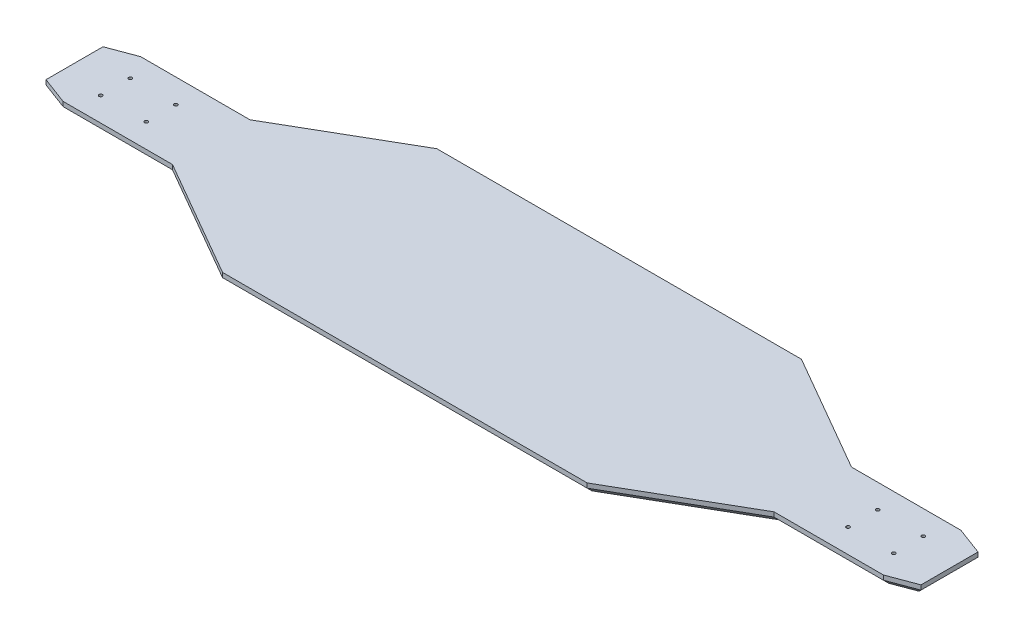
SolidWorks part; units mm, degrees
ref_plane "Front Plane" through (0, 0, 0) normal (0, 0, 1) x (1, 0, 0)
ref_plane "Top Plane" through (0, 0, 0) normal (0, 1, 0) x (1, 0, 0)
ref_plane "Right Plane" through (0, 0, 0) normal (1, 0, 0) x (0, 0, -1)
sketch "Sketch1" plane through (0, 0, 0) normal (0, 1, 0) x (1, 0, 0)
  line L0 (-241.1419, 54.734) -> (368.336, 54.734) construction
  line L1 (-241.1419, 15.0465) -> (-241.1419, 94.4215)
  line L2 (114.336, -94.491) -> (368.336, -94.491)
  line L3 (368.336, -94.491) -> (368.336, 54.734) construction
  line L4 (-50.6419, 108.709) -> (114.336, 203.959)
  line L5 (-203.0419, 108.709) -> (-241.1419, 94.4215)
  line L6 (-203.0419, 108.709) -> (-50.6419, 108.709)
  line L7 (-203.0419, 0.759) -> (-50.6419, 0.759)
  line L8 (114.336, 203.959) -> (368.336, 203.959)
  line L9 (787.3138, 0.759) -> (622.336, -94.491)
  line L10 (-203.0419, 0.759) -> (-241.1419, 15.0465)
  line L11 (-50.6419, 0.759) -> (114.336, -94.491)
  line L12 (939.7138, 0.759) -> (977.8138, 15.0465)
  line L13 (622.336, 203.959) -> (368.336, 203.959)
  line L14 (939.7138, 0.759) -> (787.3138, 0.759)
  line L15 (939.7138, 108.709) -> (787.3138, 108.709)
  line L16 (939.7138, 108.709) -> (977.8138, 94.4215)
  line L17 (787.3138, 108.709) -> (622.336, 203.959)
  line L18 (622.336, -94.491) -> (368.336, -94.491)
  line L19 (977.8138, 15.0465) -> (977.8138, 94.4215)
  dimension "D2" = 149.225
  dimension "D3" = 152.4
  dimension "D4" = 38.1
  dimension "D5" = 254
  dimension "D6" = 79.375
  dimension "D7" = 150
  dimension "D8" = 14.2875
  dimension "D10" = 190.5
extrude "Boss-Extrude1" add sketch "Sketch1" along normal blind 15.24
sketch "Sketch2" plane through (0, 0, 0) normal (0, -1, 0) x (-1, 0, 0)
  line L0 (241.1419, 54.734) -> (-37.1273, 54.734) construction
  line L1 (241.1419, 94.4215) -> (241.1419, 15.0465) construction
  line L2 (-368.336, -94.491) -> (-368.336, 203.959) construction
  line L3 (-114.336, -94.491) -> (-622.336, -94.491) construction
  line L4 (-622.336, 203.959) -> (-114.336, 203.959) construction
  line L5 (120.4919, 75.3715) -> (120.4919, 34.0965) construction
  line L6 (120.4919, 34.0965) -> (183.9919, 34.0965) construction
  line L7 (183.9919, 34.0965) -> (183.9919, 75.3715) construction
  line L8 (183.9919, 75.3715) -> (120.4919, 75.3715) construction
  circle A0 centre (183.9919, 34.0965) radius 2.3813
  circle A1 centre (183.9919, 75.3715) radius 2.3813
  circle A2 centre (120.4919, 75.3715) radius 2.3812
  circle A3 centre (120.4919, 34.0965) radius 2.3813
  circle A4 centre (-857.1638, 75.3715) radius 2.3813
  circle A5 centre (-920.6638, 75.3715) radius 2.3812
  circle A6 centre (-920.6638, 34.0965) radius 2.3812
  circle A7 centre (-857.1638, 34.0965) radius 2.3812
  point P29 (50.6419, 108.709)
  dimension "D1" = 57.15
  dimension "D2" = 63.5
  dimension "D3" = 41.275
  dimension "D4" = 20.6375
extrude "Cut-Extrude1" cut sketch "Sketch2" against normal blind 15.24
chamfer "Chamfer1" distance 8.89 angle 45 16 edges at (-126.8419, 0, -0.759) (-222.0919, 0, -7.9028) (-241.1419, 0, -54.734) (-222.0919, 0, -101.5653) (-126.8419, 0, -108.709) (31.8471, 0, -156.334) (31.8471, 0, 46.866) (368.336, 0, 94.491) (704.8249, 0, 46.866) (863.5138, 0, -0.759) (958.7638, 0, -7.9028) (977.8138, 0, -54.734) (958.7638, 0, -101.5653) (863.5138, 0, -108.709) (704.8249, 0, -156.334) (368.336, 0, -203.959)
sketch "Sketch3" plane through (0, 0, 0) normal (0, -1, 0) x (1, 0, 0)
  line L0 (962.5738, -54.734) -> (-232.2519, -54.734) construction
  line L1 (-232.2519, -21.2073) -> (-232.2519, -88.2607) construction
  line L2 (368.336, -195.069) -> (368.336, 85.601) construction
  line L3 (116.7181, -195.069) -> (619.9539, -195.069) construction
  line L4 (619.9539, 85.601) -> (116.7181, 85.601) construction
  line L5 (277.3193, -181.734) -> (277.3193, -54.734) construction
  line L6 (270.9693, -175.384) -> (127.036, -175.384) construction
  line L7 (270.9693, -175.384) -> (270.9693, -54.734) construction
  line L8 (114.336, -188.084) -> (114.336, -54.734) construction
  line L9 (120.686, -181.734) -> (120.686, -54.734) construction
  line L10 (120.686, -181.734) -> (277.3193, -181.734) construction
  line L11 (127.036, -175.384) -> (127.036, -54.734) construction
  line L12 (283.6693, -188.084) -> (283.6693, -54.734) construction
  line L13 (453.0027, -195.069) -> (453.0027, -54.734) construction
  line L14 (199.0027, -181.734) -> (199.0027, -54.734) construction
  line L15 (188.4193, -175.384) -> (188.4193, -143.634) construction
  line L16 (188.4193, -143.634) -> (137.6193, -143.634) construction
  line L17 (137.6193, -143.634) -> (137.6193, -175.384) construction
  line L18 (137.6193, -175.384) -> (188.4193, -175.384) construction
  line L20 (163.0193, -175.384) -> (163.0193, -54.734) construction
  line L32 (-118.1106, -34.0965) -> (-232.2519, -34.0965) construction
  line L33 (-120.4919, -75.3715) -> (-232.2519, -75.3715) construction
  line L36 (120.121, 72.901) -> (-44.8568, -22.349)
  line L37 (-44.8568, -22.349) -> (-199.1268, -22.349)
  line L38 (-199.1268, -22.349) -> (-219.5519, -30.0084)
  line L39 (-219.5519, -30.0084) -> (-219.5519, -79.4596)
  line L40 (-219.5519, -79.4596) -> (-199.1268, -87.119)
  line L41 (-199.1268, -87.119) -> (-44.8568, -87.119)
  line L42 (-44.8568, -87.119) -> (120.121, -182.369)
  line L43 (120.121, -182.369) -> (616.551, -182.369)
  line L44 (616.551, -182.369) -> (781.5288, -87.119)
  line L45 (781.5288, -87.119) -> (935.7988, -87.119)
  line L46 (935.7988, -87.119) -> (956.2238, -79.4596)
  line L47 (956.2238, -79.4596) -> (956.2238, -30.0084)
  line L80 (956.2238, -30.0084) -> (935.7988, -22.349)
  line L81 (935.7988, -22.349) -> (781.5288, -22.349)
  line L82 (781.5288, -22.349) -> (616.551, 72.901)
  line L83 (616.551, 72.901) -> (120.121, 72.901)
  line L84 (120.121, 72.901) -> (-44.8568, -22.349)
  line L85 (-44.8568, -22.349) -> (-199.1268, -22.349)
  line L86 (-199.1268, -22.349) -> (-219.5519, -30.0084)
  line L87 (-219.5519, -30.0084) -> (-219.5519, -79.4596)
  line L88 (-219.5519, -79.4596) -> (-199.1268, -87.119)
  line L89 (-199.1268, -87.119) -> (-44.8568, -87.119)
  line L99 (368.336, 72.901) -> (120.121, 72.901)
  circle A0 centre (-219.5519, -75.3715) radius 2.7305
  circle A1 centre (-3.6124, -110.9315) radius 2.7305
  circle A2 centre (37.6321, -134.744) radius 2.7305
  circle A3 centre (-120.4919, -34.0965) radius 2.3813 construction
  circle A4 centre (120.686, -130.934) radius 2.7305
  circle A5 centre (-206.8519, -75.3715) radius 2.7305
  circle A6 centre (120.686, -181.734) radius 2.7305
  circle A7 centre (78.8765, -158.5565) radius 2.7305
  circle A8 centre (120.686, -80.134) radius 2.7305
  circle A9 centre (172.8971, -181.734) radius 2.7305
  circle A10 centre (225.1082, -181.734) radius 2.7305
  circle A11 centre (277.3193, -80.134) radius 2.7305
  circle A12 centre (277.3193, -130.934) radius 2.7305
  circle A13 centre (-44.8568, -87.119) radius 2.7305
  circle A14 centre (277.3193, -181.734) radius 2.7305
  circle A15 centre (188.4193, -143.634) radius 2.7305
  circle A16 centre (137.6193, -143.634) radius 2.7305
  circle A17 centre (137.6193, -148.5793) radius 2.7305
  point P78 (199.0027, -175.384)
  dimension "D2" = 169.3333
  dimension "D7" = 6.35
  dimension "D13" = 3
  dimension "D3" = 12.7
  dimension "D5" = 6.35
  dimension "D6" = 6.35
  dimension "D8" = 6.35
  dimension "D9" = 6.35
  dimension "D10" = 169.3333
  dimension "D11" = 84.6667
  dimension "D12" = 25.4
  dimension "D14" = 156.6333
  dimension "D15" = 52.2111
  dimension "D16" = 52.2111
  dimension "D17" = 31.75
  dimension "D18" = 50.8
  dimension "D19" = 88.9
  dimension "D20" = 25.4
  dimension "D21" = 35.9833
  dimension "D22" = 0
  dimension "D4" = 12.7
